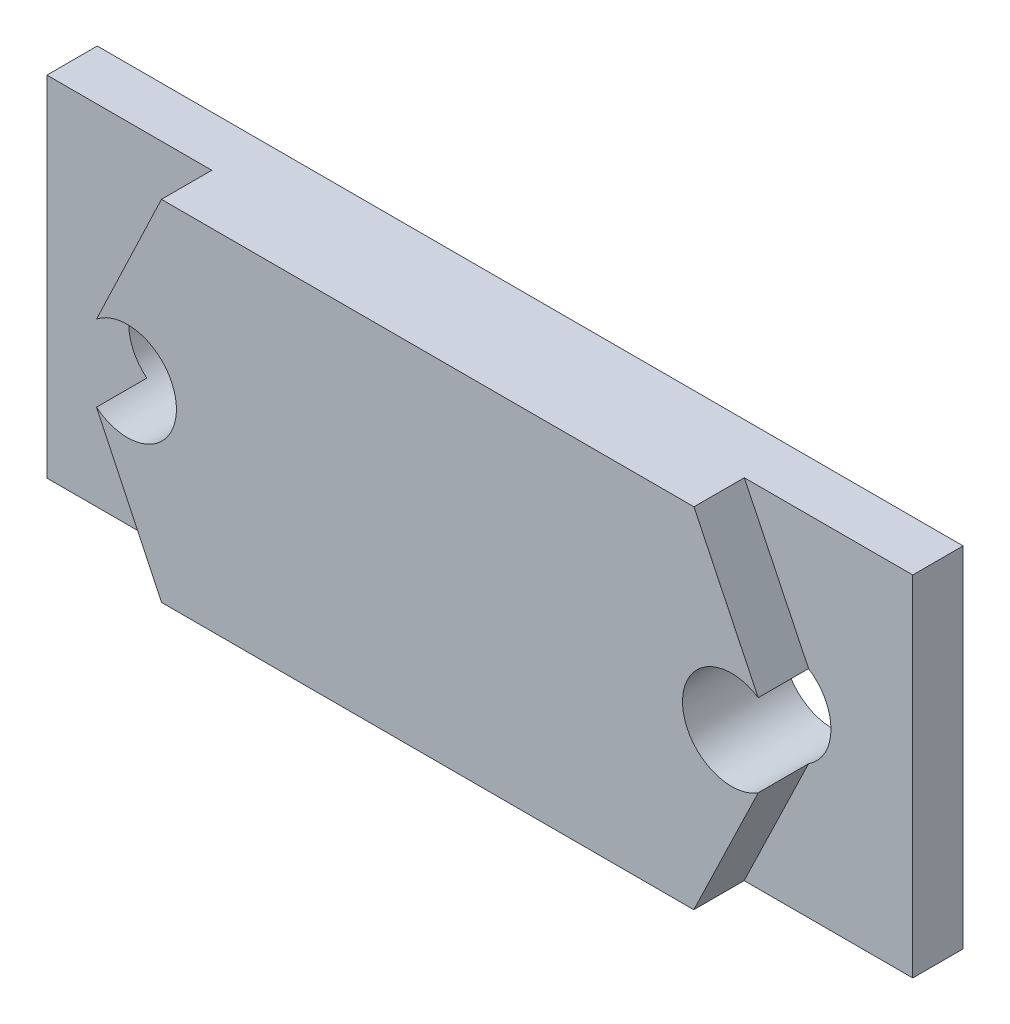
SolidWorks part; units mm, degrees
ref_plane "Front Plane" through (0, 0, 0) normal (0, 0, 1) x (1, 0, 0)
ref_plane "Top Plane" through (0, 0, 0) normal (0, 1, 0) x (1, 0, 0)
ref_plane "Right Plane" through (0, 0, 0) normal (1, 0, 0) x (0, 0, -1)
sketch "Sketch3" plane through (0, 0, 0) normal (0, 0, 1) x (-1, 0, 0)
  line L0 (-31.8245, 17.4865) -> (2.5676, 17.4865)
  line L1 (-31.8245, 17.4865) -> (-31.8245, 3.6218)
  line L2 (2.5676, 17.4865) -> (2.5676, 3.6218)
  line L3 (-31.8245, 3.6218) -> (2.5676, 3.6218)
  circle A0 centre (-26.6284, 10.5478) radius 1.9483
  circle A1 centre (-2.6284, 10.5478) radius 1.9483
extrude "Boss-Extrude1" add sketch "Sketch3" along normal blind 4
sketch "Sketch4" plane through (0, 0, 4) normal (0, 0, 1) x (1, 0, 0)
  line L0 (-2.5676, -3.6218) -> (-2.5676, -17.4865)
  line L1 (31.8245, -17.4865) -> (31.8245, -3.6218)
  line L3 (3.9873, -3.6091) -> (-2.5676, -3.6091)
  line L4 (3.9873, -17.4865) -> (-2.5676, -17.4865)
  line L5 (-2.5676, -3.6091) -> (-2.5676, -17.4865)
  line L6 (3.9873, -3.6091) -> (-2.5676, -17.4865) construction
  line L7 (3.9873, -17.4865) -> (-2.5676, -3.6091) construction
  line L8 (3.9873, -17.4865) -> (0.6802, -10.5478)
  line L9 (0.6802, -10.5478) -> (3.9873, -3.6091)
  line L11 (25.1281, -3.6091) -> (31.8245, -3.6091)
  line L12 (25.1281, -17.4865) -> (31.8245, -17.4865)
  line L13 (31.8245, -3.6091) -> (31.8245, -17.4865)
  line L14 (25.1281, -3.6091) -> (31.8245, -17.4865) construction
  line L15 (25.1281, -17.4865) -> (31.8245, -3.6091) construction
  line L16 (25.1281, -17.4865) -> (28.4763, -10.5478)
  line L17 (28.4763, -10.5478) -> (25.1281, -3.6091)
  circle A0 centre (2.6284, -10.5478) radius 1.9483 construction
  point P9 (0.7099, -10.5478)
  point P16 (28.4763, -10.5478)
extrude "Cut-Extrude2" cut sketch "Sketch4" against normal blind 2 contours L6 L9 L3 L4 L5 L8 | L17 L0 L16 L5 L1 L3
